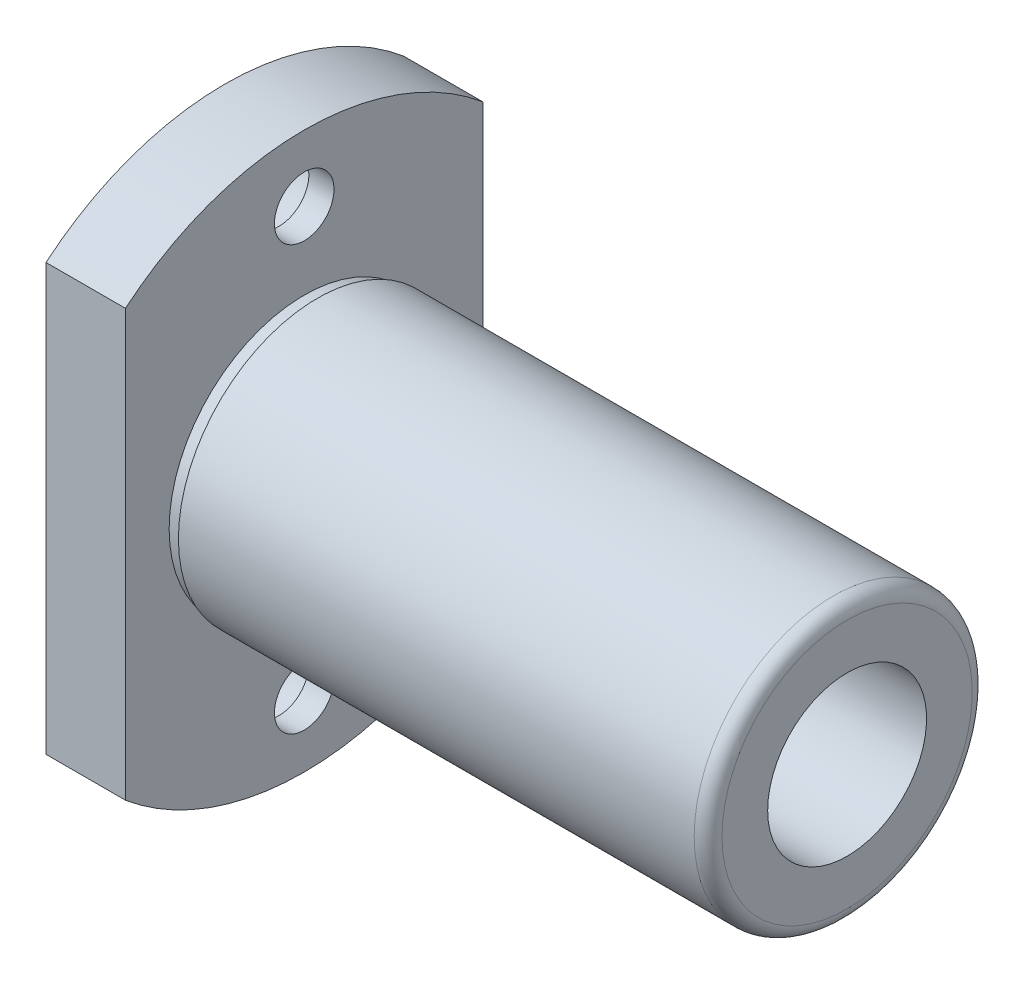
SolidWorks part; units mm, degrees
material "Chrome Stainless Steel"
ref_plane "Front Plane" through (0, 0, 0) normal (0, 0, 1) x (1, 0, 0)
ref_plane "Top Plane" through (0, 0, 0) normal (0, 1, 0) x (1, 0, 0)
ref_plane "Right Plane" through (0, 0, 0) normal (1, 0, 0) x (0, 0, -1)
ref_plane "Plane1" through (0, 0, 0) normal (0, 0, 1) x (1, 0, 0)
sketch "Sketch1" plane through (0, 0, 0) normal (0, 0, 1) x (1, 0, 0)
  line L0 (0, 21) -> (0, 6)
  line L1 (0, 6) -> (47, 6)
  line L2 (47, 6) -> (47, 9.45)
  line L3 (45.95, 10.5) -> (7, 10.5)
  line L4 (7, 10.5) -> (7, 10.2)
  line L5 (7, 10.2) -> (6, 10.2)
  line L6 (6, 10.2) -> (6, 21)
  line L7 (6, 21) -> (0, 21)
  line L8 (47, 0) -> (0, 0) construction
  arc A0 (47, 9.45) -> (45.95, 10.5) centre (45.95, 9.45) ccw
revolve "Revolve1" add sketch "Sketch1" angle 360 about L8
ref_plane "Plane2" through (0, 0, 0) normal (1, 0, 0) x (0, 0, -1)
sketch "Sketch2" plane through (0, 0, 0) normal (1, 0, 0) x (0, 0, -1)
  line L0 (-42, 42) -> (-42, -42)
  line L1 (-42, -42) -> (42, -42)
  line L2 (42, -42) -> (42, 42)
  line L3 (42, 42) -> (-42, 42)
  line L4 (13.5, -16.0857) -> (13.5, 16.0857)
  line L5 (-13.5, 16.0857) -> (-13.5, -16.0857)
  arc A0 (-13.5, -16.0857) -> (13.5, -16.0857) centre (0, 0) ccw
  arc A1 (13.5, 16.0857) -> (-13.5, 16.0857) centre (0, 0) ccw
extrude "Cut-Extrude1" cut sketch "Sketch2" along normal blind 6
ref_plane "Plane3" through (0, 0, 0) normal (0, 0, 1) x (1, 0, 0)
sketch "Sketch3" plane through (0, 0, 0) normal (0, 0, 1) x (1, 0, 0)
  line L0 (0, 16) -> (0, 19.75)
  line L1 (0, 19.75) -> (4.1, 19.75)
  line L2 (4.1, 19.75) -> (4.1, 18.25)
  line L3 (4.1, 18.25) -> (6, 18.25)
  line L4 (6, 18.25) -> (6, 16)
  line L5 (6, 16) -> (0, 16)
  line L6 (6, 16) -> (0, 16) construction
revolve "Cut-Revolve1" cut sketch "Sketch3" angle 360 about L6
ref_plane "Plane4" through (0, 0, 0) normal (0, 0, 1) x (1, 0, 0)
sketch "Sketch4" plane through (0, 0, 0) normal (0, 0, 1) x (1, 0, 0)
  line L0 (0, -16) -> (0, -12.25)
  line L1 (0, -12.25) -> (4.1, -12.25)
  line L2 (4.1, -12.25) -> (4.1, -13.75)
  line L3 (4.1, -13.75) -> (6, -13.75)
  line L4 (6, -13.75) -> (6, -16)
  line L5 (6, -16) -> (0, -16)
  line L6 (6, -16) -> (0, -16) construction
revolve "Cut-Revolve2" cut sketch "Sketch4" angle 360 about L6
